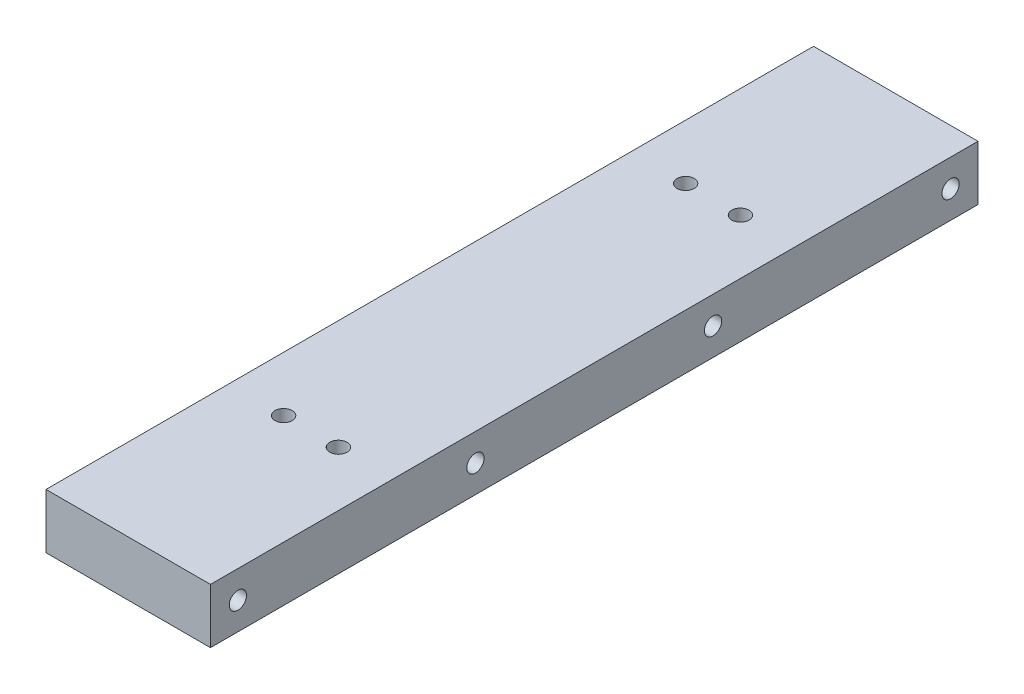
SolidWorks part; units mm, degrees
material "TPU"
ref_plane "Front Plane" through (0, 0, 0) normal (0, 0, 1) x (1, 0, 0)
ref_plane "Top Plane" through (0, 0, 0) normal (0, 1, 0) x (1, 0, 0)
ref_plane "Right Plane" through (0, 0, 0) normal (1, 0, 0) x (0, 0, -1)
sketch "Sketch2" plane through (0, 0, 0) normal (0, 1, 0) x (1, 0, 0)
  line L0 (0, 0) -> (28.575, 0)
  line L1 (28.575, 0) -> (28.575, 133.35)
  line L2 (28.575, 133.35) -> (0, 133.35)
  line L3 (0, 133.35) -> (0, 0)
  dimension "D1" = 133.35
  dimension "D2" = 28.575
extrude "Boss-Extrude1" add sketch "Sketch2" along normal blind 9.525
sketch "Sketch3" plane through (28.575, 0, 0) normal (1, 0, 0) x (0, 0, -1)
  line L0 (0, 9.525) -> (0, 0) construction
  line L1 (0, 9.525) -> (133.35, 9.525) construction
  point P0 (4.7625, 4.7625)
  dimension "D1" = 4.7625
  dimension "D2" = 4.7625
sketch "Sketch4" plane through (28.575, 0, 0) normal (1, 0, 0) x (0, 0, -1)
  point P0 (4.7625, 4.7625)
hole_wizard "Ø3.0mm Dowel Hole1" positions "Sketch4" profile "Sketch5" hole size "Ø3.0" standard "ANSI Metric" end condition through all
sketch "Sketch5" plane through (28.575, 4.7625, -4.7625) normal (0, 1, 0) x (0, 0, -1)
  line L0 (0, 0) -> (0, 28.575)
  line L1 (0, 28.575) -> (1.5, 28.575)
  line L2 (1.5, 28.575) -> (1.5, 0)
  line L5 (1.5, 0) -> (0, 0)
  line L11 (0, -6.35) -> (0, 107.95) construction
  dimension "Thru Hole Dia." = 3
  dimension "Thru Hole Depth" = 28.575
pattern_linear "LPattern1" count 4 spacing 41.275 along (0, 0, -1) of "Ø3.0mm Dowel Hole1"
sketch "Sketch8" plane through (0, 0, 0) normal (0, -1, 0) x (1, 0, 0)
  line L0 (0, 0) -> (14.2875, 0)
  line L1 (0, 0) -> (28.575, 0) construction
  line L2 (28.575, -133.35) -> (0, -133.35) construction
  line L3 (0, -133.35) -> (0, 0) construction
  line L4 (28.575, 0) -> (28.575, -133.35) construction
  circle A0 centre (9.525, -31.75) radius 1.5
  circle A1 centre (9.525, -101.6) radius 1.5
  circle A2 centre (19.05, -101.6) radius 1.5
  circle A3 centre (19.05, -31.75) radius 1.5
  point P5 (9.525, -31.75)
  point P6 (9.525, -101.6)
  point P15 (19.05, -31.75)
  point P16 (19.05, -101.6)
  dimension "D5" = 3
  dimension "D6" = 3
  dimension "D11" = 3
  dimension "D12" = 3
  dimension "D1" = 31.75
  dimension "D2" = 31.75
  dimension "D3" = 9.525
  dimension "D4" = 9.525
  dimension "D7" = 9.525
  dimension "D8" = 9.525
  dimension "D9" = 31.75
  dimension "D10" = 31.75
extrude "Cut-Extrude2" cut sketch "Sketch8" against normal through all contours A0 | A1 | A2 | A3
